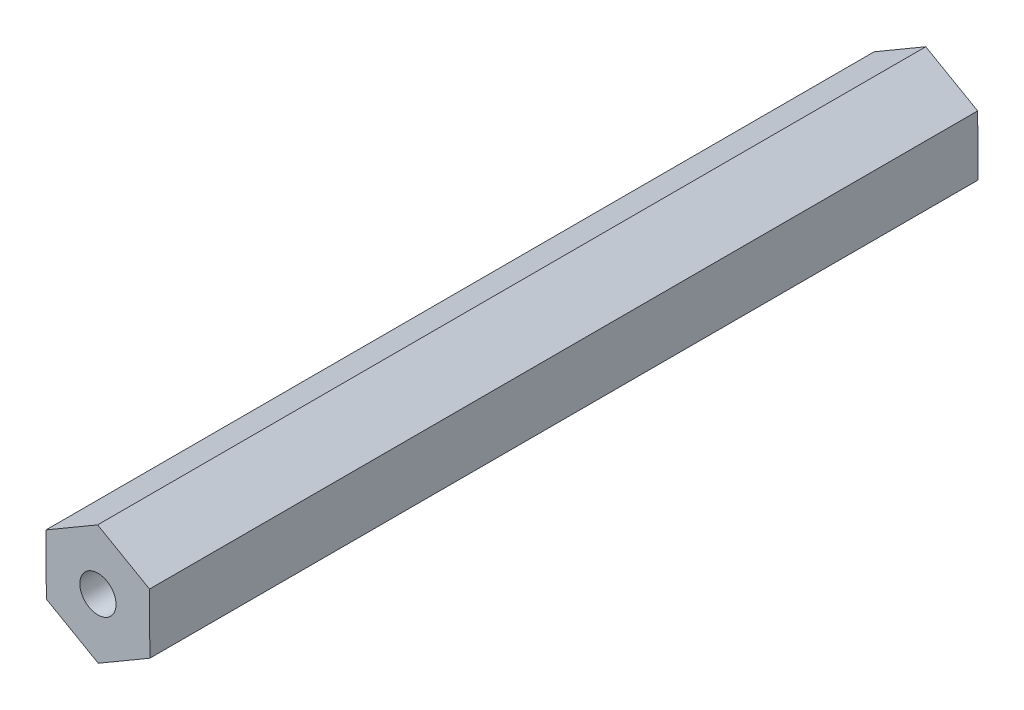
SolidWorks part; units mm, degrees
material "PE High Density"
ref_plane "Front Plane" through (0, 0, 0) normal (0, 0, 1) x (1, 0, 0)
ref_plane "Top Plane" through (0, 0, 0) normal (0, 1, 0) x (1, 0, 0)
ref_plane "Right Plane" through (0, 0, 0) normal (1, 0, 0) x (0, 0, -1)
sketch "Sketch1" plane through (0, 0, 0) normal (0, 0, 1) x (1, 0, 0)
  line L1 (2.5076, -1.4301) -> (2.4923, 1.4566)
  line L2 (2.4923, 1.4566) -> (-0.0153, 2.8867)
  line L3 (-0.0153, 2.8867) -> (-2.5076, 1.4301)
  line L4 (-2.5076, 1.4301) -> (-2.4923, -1.4566)
  line L5 (-2.4923, -1.4566) -> (0.0153, -2.8867)
  line L6 (0.0153, -2.8867) -> (2.5076, -1.4301)
  circle A0 centre (0, 0) radius 2.5 construction
  dimension "D1" = 5
extrude "Boss-Extrude1" add sketch "Sketch1" along normal blind 40
hole_wizard "M2.2x0.45 Tapped Hole1" positions "Sketch4" profile "Sketch3" tap size "M2.2x0.45" standard "Ansi Metric" end condition through all
sketch "Sketch4" plane through (0, 0, 40) normal (0, 0, 1) x (1, 0, 0)
  point P0 (0, 0)
sketch "Sketch3" plane through (0, 0, 40) normal (1, 0, 0) x (0, -1, 0)
  line L0 (0, 0) -> (0, 40)
  line L1 (0, 40) -> (0.875, 40)
  line L2 (0.875, 40) -> (0.875, 0)
  line L5 (0.875, 0) -> (0, 0)
  line L11 (0, -6.35) -> (0, 107.95) construction
  dimension "Thru Tap Drill Dia." = 1.75
  dimension "Thru Tap Drill Depth" = 40
cosmetic thread "Hole Thread1"
